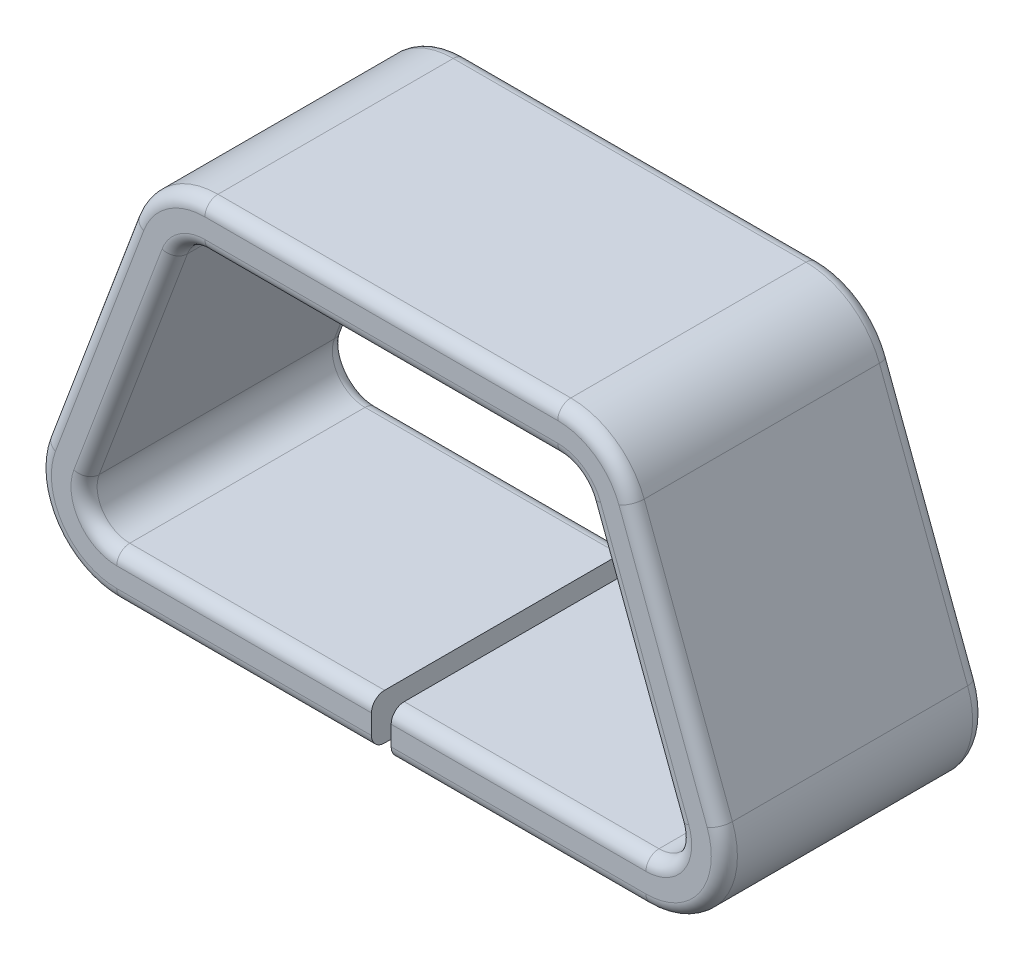
SolidWorks part; units mm, degrees
ref_plane "Front Plane" through (0, 0, 0) normal (0, 0, 1) x (1, 0, 0)
ref_plane "Top Plane" through (0, 0, 0) normal (0, 1, 0) x (1, 0, 0)
ref_plane "Right Plane" through (0, 0, 0) normal (1, 0, 0) x (0, 0, -1)
ref_plane "Plane1" through (0, 0, 0) normal (0, 0, 1) x (1, 0, 0)
sketch "Sketch1" plane through (0, 0, 0) normal (0, 0, 1) x (1, 0, 0)
  line L0 (-0.6858, 1.524) -> (0.6858, 1.524)
  line L1 (-1.0287, 0) -> (1.0287, 0)
  line L2 (-0.9712, 1.3262) -> (-1.3141, 0.4118)
  line L3 (0.9712, 1.3262) -> (1.3141, 0.4118)
  arc A0 (0.9712, 1.3262) -> (0.6858, 1.524) centre (0.6858, 1.2192) ccw
  arc A1 (-0.6858, 1.524) -> (-0.9712, 1.3262) centre (-0.6858, 1.2192) ccw
  arc A2 (-1.3141, 0.4118) -> (-1.0287, 0) centre (-1.0287, 0.3048) ccw
  arc A3 (1.0287, 0) -> (1.3141, 0.4118) centre (1.0287, 0.3048) ccw
  point P2 (0, 1.524)
  point P5 (0, 0)
extrude "Boss-Extrude1" add sketch "Sketch1" along normal blind 1.016
shell "Shell1" thickness 0.1778
sketch "Sketch2" plane through (0, 0, 0) normal (0, -1, 0) x (1, 0, 0)
  line L0 (-0.0383, -0.0656) -> (-0.0383, 1.0816)
  line L1 (-0.0383, 1.0816) -> (0.0383, 1.0816)
  line L2 (0.0383, 1.0816) -> (0.0383, -0.0656)
  line L3 (0.0383, -0.0656) -> (-0.0383, -0.0656)
  point P4 (0, -0.0656)
extrude "Cut-Extrude1" cut sketch "Sketch2" against normal blind 0.8128
fillet "Fillet7" radius 0.0508 38 edges at (0.5335, 0.1778, 1.016) (1.1331, 0.2325, 1.016) (0.9762, 0.8066, 1.016) (0.7581, 1.3236, 1.016) (0, 1.3462, 1.016) (-0.7581, 1.3236, 1.016) (-0.5335, 0.1778, 1.016) (-1.1331, 0.2325, 1.016) (0.5335, 0, 1.016) (1.2792, 0.1312, 1.016) (1.1426, 0.869, 1.016) (0.8594, 1.4697, 1.016) (0, 1.524, 1.016) (-0.8594, 1.4697, 1.016) (-0.5335, 0, 1.016) (-1.2792, 0.1312, 1.016) (-1.1331, 0.2325, 0) (-0.9762, 0.8066, 0) (-0.7581, 1.3236, 0) (0, 1.3462, 0) (0.7581, 1.3236, 0) (0.9762, 0.8066, 0) (1.1331, 0.2325, 0) (0.5335, 0.1778, 0) (0.0383, 0.0889, 0) (0.5335, 0, 0) (1.2792, 0.1312, 0) (1.1426, 0.869, 0) (0.8594, 1.4697, 0) (0, 1.524, 0) (-0.8594, 1.4697, 0) (-1.1426, 0.869, 0) (-1.2792, 0.1312, 0) (-0.5335, 0, 0) (-0.0383, 0.0889, 0) (-0.5335, 0.1778, 0) (-0.9762, 0.8066, 1.016) (-1.1426, 0.869, 1.016)
